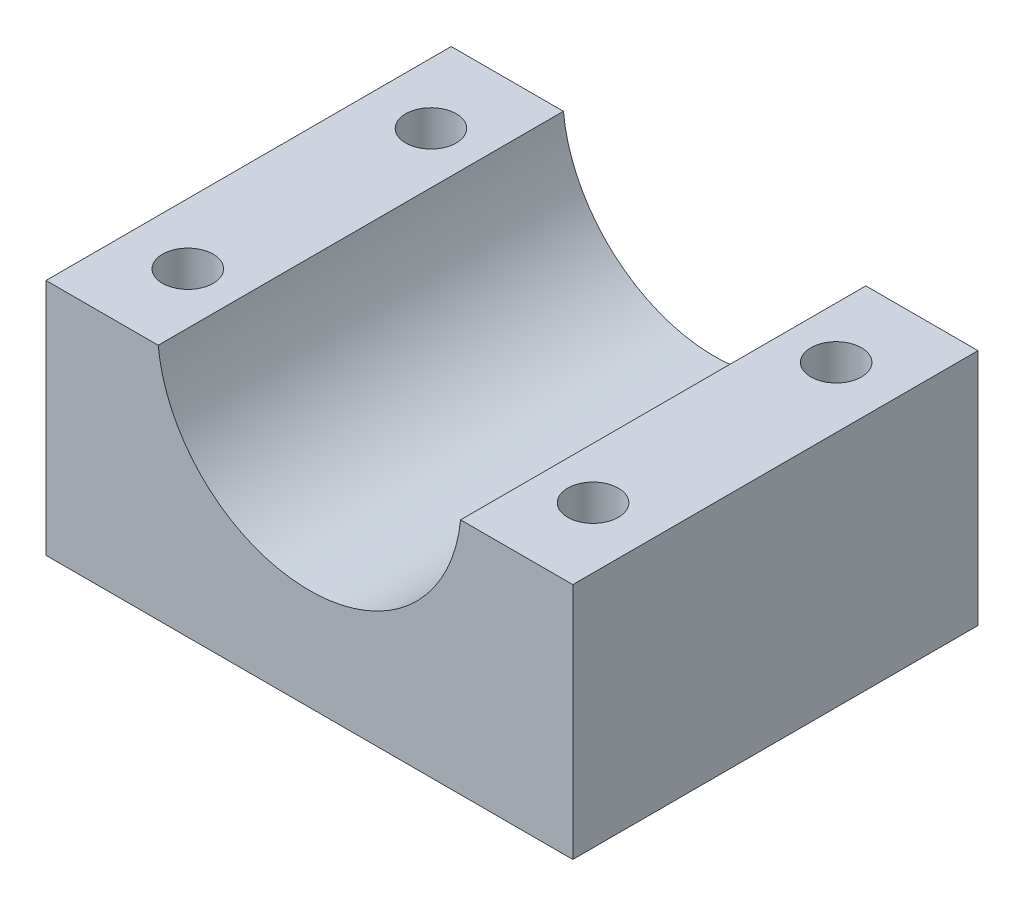
SolidWorks part; units mm, degrees
ref_plane "Front Plane" through (0, 0, 0) normal (0, 0, 1) x (1, 0, 0)
ref_plane "Top Plane" through (0, 0, 0) normal (0, 1, 0) x (1, 0, 0)
ref_plane "Right Plane" through (0, 0, 0) normal (1, 0, 0) x (0, 0, -1)
sketch "Sketch1" plane through (0, 0, 0) normal (0, 0, 1) x (1, 0, 0)
  line L1 (0, 0) -> (52, 0)
  line L2 (0, 0) -> (0, 23.5)
  line L3 (0, 23.5) -> (52, 23.5)
  line L4 (52, 0) -> (52, 23.5)
  circle A0 centre (26, 25) radius 15
  dimension "D3" = 30
  dimension "D1" = 52
  dimension "D2" = 23.5
  dimension "D4" = 25
  dimension "D5" = 26
extrude "Boss-Extrude1" add sketch "Sketch1" along normal blind 40 contours A0 L3 L2 L1 L4
sketch "Sketch2" plane through (0, 0, 0) normal (0, -1, 0) x (-1, 0, 0)
  line L1 (0, -40) -> (0, 0) construction
  line L2 (-52, -40) -> (-52, 0) construction
  line L4 (0, -40) -> (-52, -40) construction
  line L5 (0, 0) -> (-52, 0) construction
  circle A0 centre (-6, -8) radius 2.5
  circle A1 centre (-6, -32) radius 2.5
  circle A2 centre (-46, -32) radius 2.5
  circle A3 centre (-46, -8) radius 2.5
  dimension "D1" = 5
  dimension "D2" = 5
  dimension "D3" = 5
  dimension "D4" = 5
  dimension "D5" = 6
  dimension "D6" = 40
  dimension "D7" = 6
  dimension "D8" = 6
  dimension "D9" = 8
  dimension "D10" = 8
  dimension "D11" = 8
  dimension "D12" = 8
extrude "Cut-Extrude1" cut sketch "Sketch2" against normal up to surface (23.5 mm away) up to face at (46.4624, 23.5, 20)
